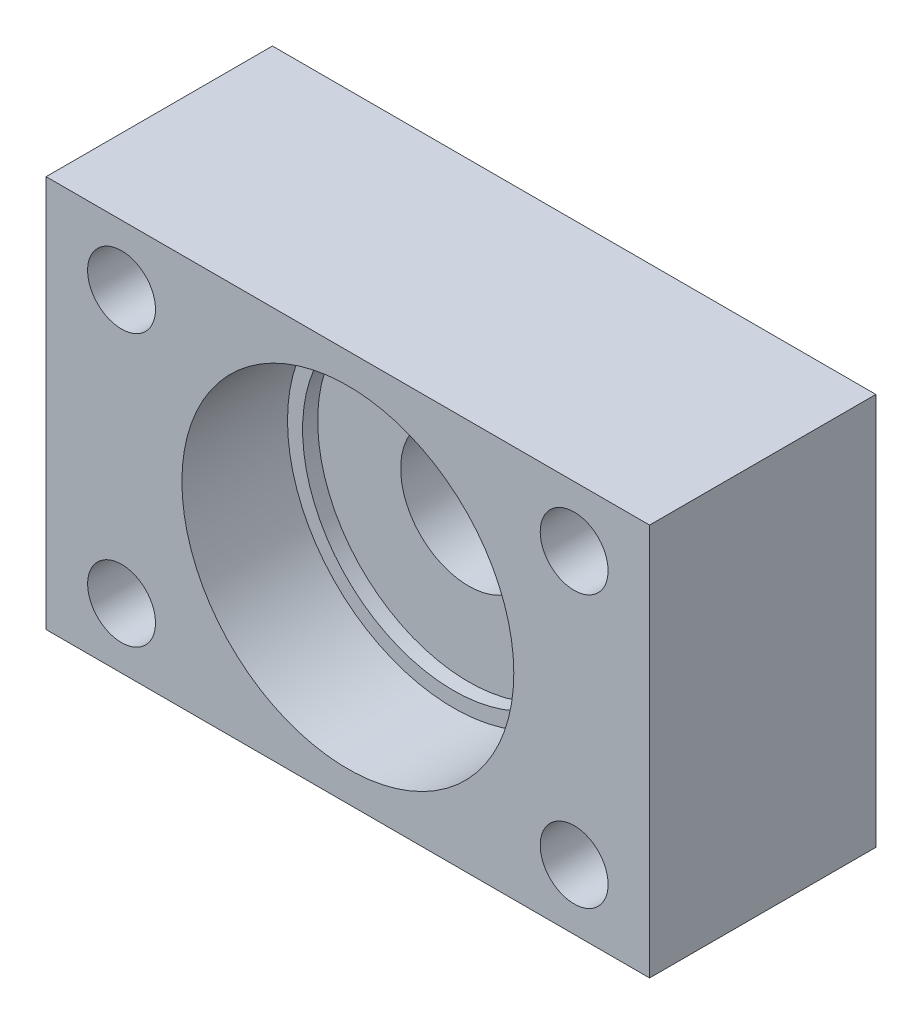
SolidWorks part; units mm, degrees
ref_plane "Front" through (0, 0, 0) normal (0, 0, 1) x (1, 0, 0)
ref_plane "Top" through (0, 0, 0) normal (0, 1, 0) x (1, 0, 0)
ref_plane "Right" through (0, 0, 0) normal (1, 0, 0) x (0, 0, -1)
sketch "Esquisse1" plane through (0, 0, 0) normal (0, 0, 1) x (1, 0, 0)
  line L1 (0, 0) -> (40, 0)
  line L2 (0, 0) -> (0, 26)
  line L3 (0, 26) -> (40, 26)
  line L4 (40, 0) -> (40, 26)
  dimension "D1" = 40
  dimension "D2" = 26
extrude "Boss.-Extru.1" add sketch "Esquisse1" along normal blind 15
sketch "Esquisse2" plane through (0, 0, 15) normal (0, 0, 1) x (1, 0, 0)
  line L0 (0, 13) -> (40, 13) construction
  line L1 (0, 26) -> (0, 0) construction
  line L2 (40, 0) -> (40, 26) construction
  circle A0 centre (20, 13) radius 11
  point P8 (0, 15)
  dimension "D1" = 22
extrude "Enlèv. mat.-Extru.1" cut sketch "Esquisse2" against normal blind 7
sketch "Esquisse3" plane through (0, 0, 8) normal (0, 0, 1) x (1, 0, 0)
  circle A0 centre (20, 13) radius 10
  dimension "D1" = 20
extrude "Enlèv. mat.-Extru.2" cut sketch "Esquisse3" against normal blind 1
sketch "Esquisse4" plane through (0, 0, 7) normal (0, 0, 1) x (1, 0, 0)
  circle A0 centre (20, 13) radius 4.5
  dimension "D1" = 9
extrude "Enlèv. mat.-Extru.3" cut sketch "Esquisse4" against normal up to vertex (7 mm away) up to point (40, 26, 0)
sketch "Esquisse5" plane through (0, 0, 15) normal (0, 0, 1) x (1, 0, 0)
  line L0 (5, 0) -> (5, 26) construction
  line L1 (0, 0) -> (40, 0) construction
  line L2 (40, 26) -> (0, 26) construction
  line L3 (0, 13) -> (40, 13) construction
  line L4 (0, 26) -> (0, 0) construction
  line L5 (40, 0) -> (40, 26) construction
  line L6 (20, 13) -> (20, 26) construction
  line L7 (35, 0) -> (35, 26) construction
  circle A0 centre (5, 22) radius 2.25
  circle A1 centre (5, 4) radius 2.25
  circle A2 centre (35, 4) radius 2.25
  circle A3 centre (35, 22) radius 2.25
  dimension "D1" = 4.5
  dimension "D2" = 18
  dimension "D3" = 30
extrude "Enlèv. mat.-Extru.4" cut sketch "Esquisse5" against normal through all
